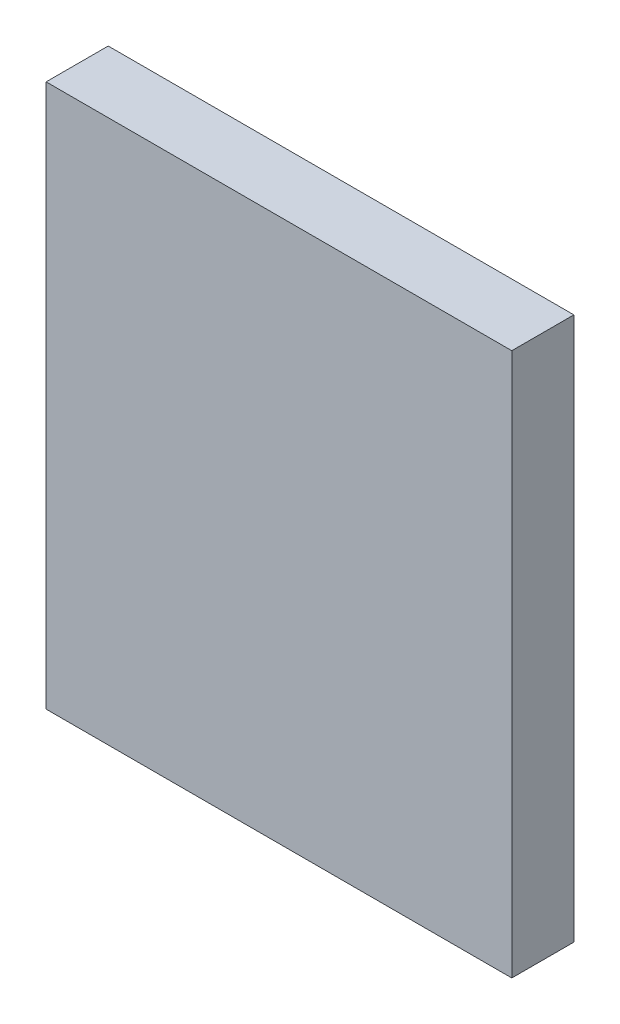
SolidWorks part; units mm, degrees
ref_plane "前视基准面" through (0, 0, 0) normal (0, 0, 1) x (1, 0, 0)
ref_plane "上视基准面" through (0, 0, 0) normal (0, 1, 0) x (1, 0, 0)
ref_plane "右视基准面" through (0, 0, 0) normal (1, 0, 0) x (0, 0, -1)
other "Configuration Table"
sketch "草图1" plane through (0, 0, 0) normal (0, 0, 1) x (1, 0, 0)
  line L1 (15, -17.5) -> (-15, -17.5)
  line L2 (15, -17.5) -> (15, 17.5)
  line L3 (15, 17.5) -> (-15, 17.5)
  line L4 (-15, -17.5) -> (-15, 17.5)
  line L5 (0, 17.5) -> (0, -17.5) construction
  line L6 (15, 0) -> (-15, 0) construction
  point P0 (0, 0)
  dimension "D1" = 30
  dimension "D2" = 35
extrude "凸台-拉伸1" add sketch "草图1" along normal blind 4
